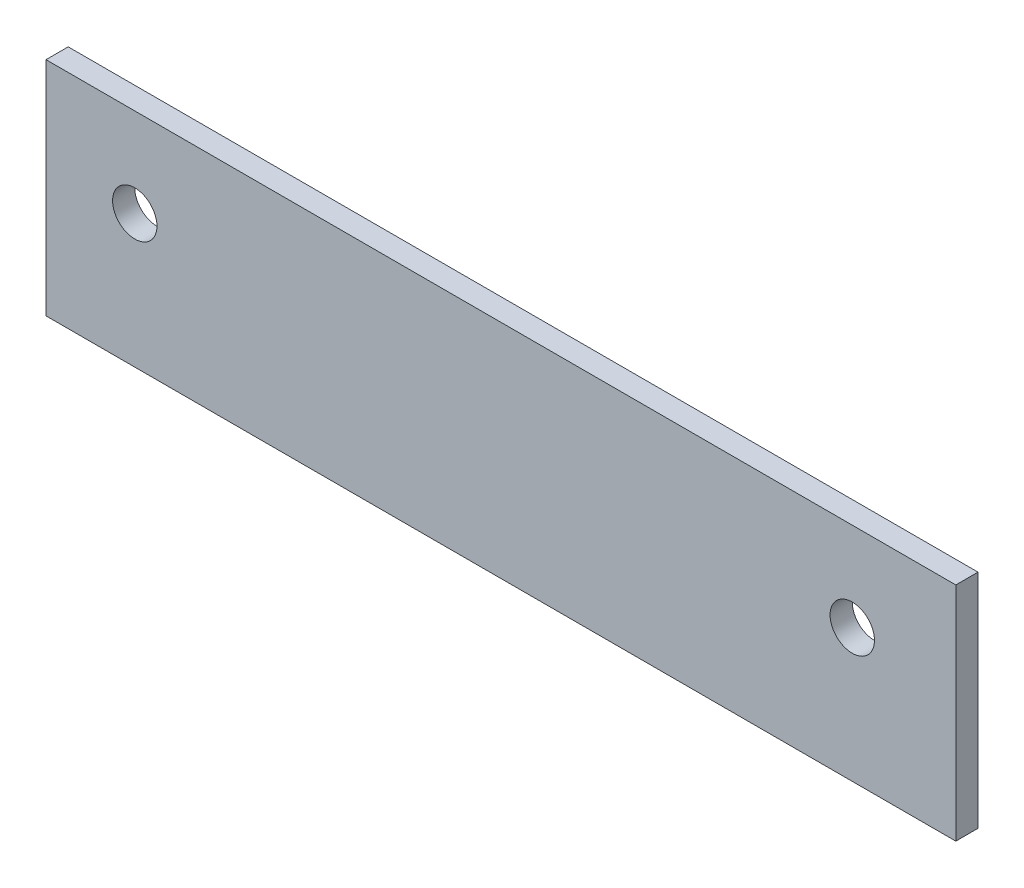
SolidWorks part; units mm, degrees
ref_plane "Plan de face" through (0, 0, 0) normal (0, 0, 1) x (1, 0, 0)
ref_plane "Plan de dessus" through (0, 0, 0) normal (0, 1, 0) x (1, 0, 0)
ref_plane "Plan de droite" through (0, 0, 0) normal (1, 0, 0) x (0, 0, -1)
sketch "Esquisse1" plane through (0, 0, 0) normal (0, 0, 1) x (1, 0, 0)
  line L1 (-26.736, 16.0435) -> (34.764, 16.0435)
  line L2 (-26.736, 16.0435) -> (-26.736, 1.0435)
  line L3 (-26.736, 1.0435) -> (34.764, 1.0435)
  line L4 (34.764, 16.0435) -> (34.764, 1.0435)
  dimension "D1" = 61.5
  dimension "D2" = 15
extrude "Extrusion1" add sketch "Esquisse1" along normal blind 1.5
sketch "Esquisse2" plane through (0, 0, 1.5) normal (0, 0, 1) x (1, 0, 0)
  line L0 (-26.736, 16.0435) -> (-26.736, 1.0435) construction
  line L1 (-26.736, 1.0435) -> (34.764, 1.0435) construction
  line L2 (34.764, 1.0435) -> (34.764, 16.0435) construction
  circle A0 centre (-20.736, 10.0435) radius 1.5
  circle A1 centre (27.764, 10.0435) radius 1.5
  dimension "D1" = 6
  dimension "D2" = 9
  dimension "D3" = 9
  dimension "D4" = 7
extrude "Extrusion2" cut sketch "Esquisse2" against normal blind 1.5
